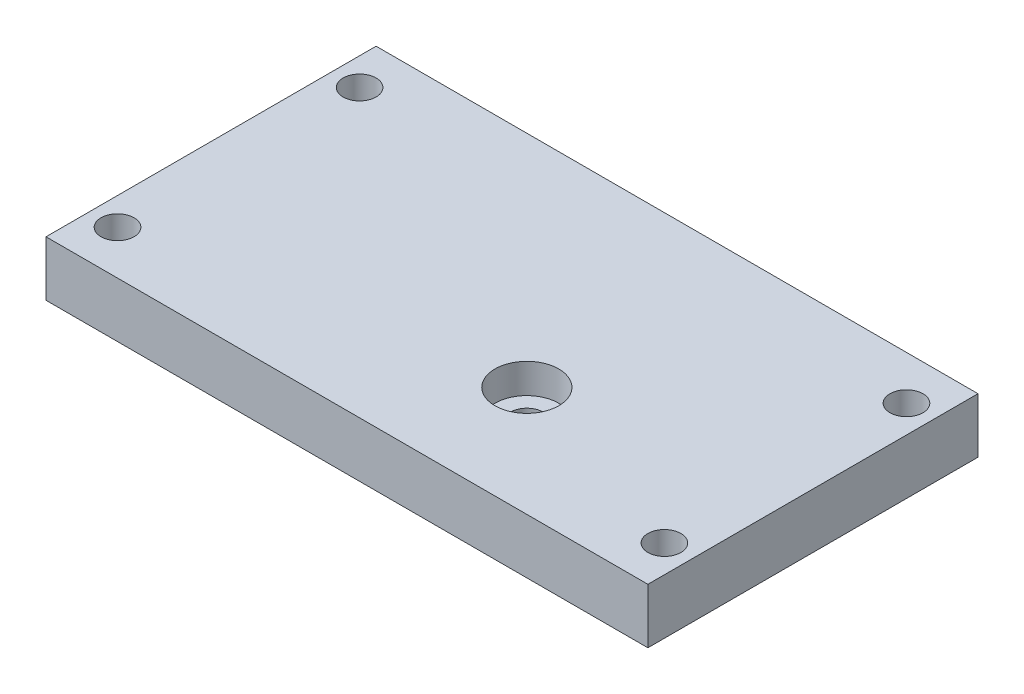
SolidWorks part; units mm, degrees
ref_plane "Plan de face" through (0, 0, 0) normal (0, 0, 1) x (1, 0, 0)
ref_plane "Plan de dessus" through (0, 0, 0) normal (0, 1, 0) x (1, 0, 0)
ref_plane "Plan de droite" through (0, 0, 0) normal (1, 0, 0) x (0, 0, -1)
sketch "Esquisse1" plane through (0, 0, 0) normal (0, 1, 0) x (1, 0, 0)
  line L1 (-49.7, 20) -> (5, 20)
  line L2 (-49.7, 20) -> (-49.7, -10)
  line L3 (-49.7, -10) -> (5, -10)
  line L4 (5, 20) -> (5, -10)
extrude "Extrusion1" add sketch "Esquisse1" along normal blind 5
sketch "Esquisse2" plane through (0, 5, 0) normal (0, 1, 0) x (1, 0, 0)
  line L0 (-49.7, -10) -> (5, -10) construction
  line L1 (5, -10) -> (5, 20) construction
  circle A0 centre (-16, 0) radius 1.5
  dimension "D1" = 3
  dimension "D2" = 10
  dimension "D3" = 21
extrude "Enlèv. mat.-Extru.1" cut sketch "Esquisse2" against normal through all
sketch "Esquisse3" plane through (0, 2.3, 0) normal (0, -1, 0) x (1, 0, 0)
  circle A0 centre (-16, 0) radius 2.9 construction
  circle A1 centre (-16, 0) radius 2.9
extrude "Enlèv. mat.-Extru.2" cut sketch "Esquisse3" against normal through all
sketch "Esquisse4" plane through (0, 5, 0) normal (0, 1, 0) x (1, 0, 0)
  line L0 (5, -10) -> (5, 20) construction
  line L1 (-49.7, -10) -> (5, -10) construction
  line L2 (5, 20) -> (-49.7, 20) construction
  line L3 (-49.7, 20) -> (-49.7, -10) construction
  circle A0 centre (2.5, -6) radius 1.5
  circle A1 centre (2.5, 16) radius 1.5
  circle A2 centre (-47.2, 16) radius 1.5
  circle A3 centre (-47.2, -6) radius 1.5
  dimension "D1" = 3
  dimension "D2" = 2.5
  dimension "D3" = 4
  dimension "D4" = 4
  dimension "D5" = 2.5
extrude "Enlèv. mat.-Extru.3" cut sketch "Esquisse4" against normal through all
